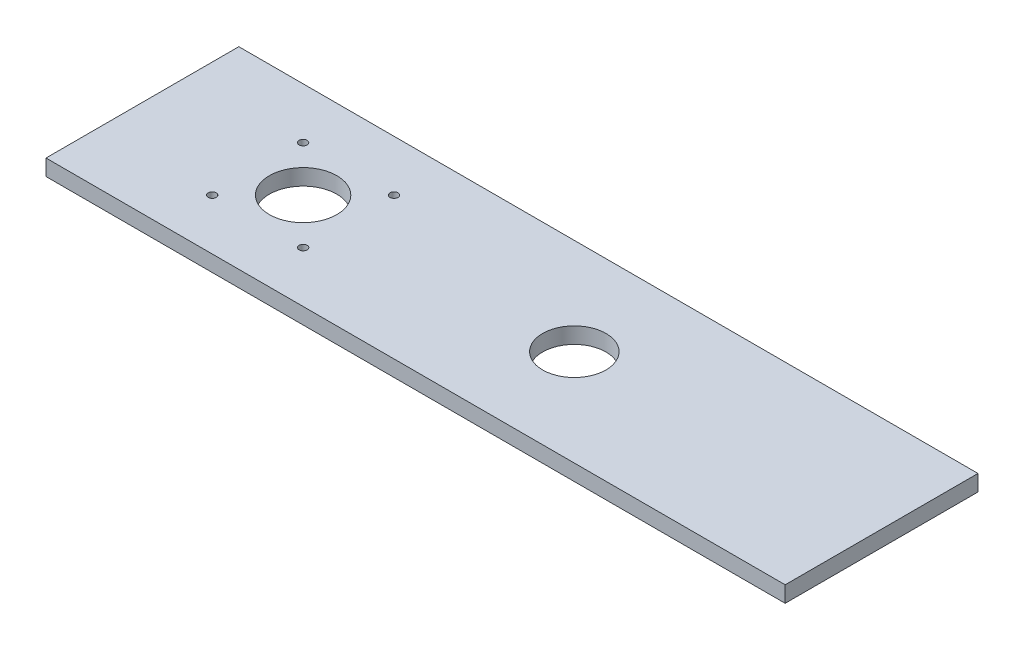
SolidWorks part; units mm, degrees
ref_plane "Front Plane" through (0, 0, 0) normal (0, 0, 1) x (1, 0, 0)
ref_plane "Top Plane" through (0, 0, 0) normal (0, 1, 0) x (1, 0, 0)
ref_plane "Right Plane" through (0, 0, 0) normal (1, 0, 0) x (0, 0, -1)
sketch "Sketch1" plane through (0, 0, 0) normal (0, 1, 0) x (1, 0, 0)
  line L0 (-50, 30) -> (180, 30)
  line L2 (-50, 30) -> (-50, -30)
  line L4 (180, 30) -> (180, -30)
  line L5 (180, -30) -> (-50, -30)
  circle A0 centre (0, 0) radius 10.5
  circle A3 centre (84.3856, 0) radius 9.8483
  point P0 (0, 0)
  dimension "D1" = 21
  dimension "D2" = 230
  dimension "D3" = 60
  dimension "D4" = 50
extrude "Boss-Extrude1" add sketch "Sketch1" along normal blind 5
hole_wizard "M3x0.5 Tapped Hole1" positions "Sketch3" profile "Sketch4" tap size "M3x0.5" standard "ANSI Metric" end condition through all
sketch "Sketch3" plane through (0, 5, 0) normal (0, 1, 0) x (1, 0, 0)
  line L4 (-14.1421, 14.1421) -> (0, 0) construction
  line L5 (0, 0) -> (0, 30) construction
  line L6 (180, 30) -> (-50, 30) construction
  point P0 (-14.1421, 14.1421)
  point P36 (14.1421, 14.1421)
  point P37 (14.1421, -14.1421)
  point P38 (-14.1421, -14.1421)
  point P39 (0, 0)
  dimension "D1" = 4
  dimension "D2" = 45
  dimension "D3" = 20
sketch "Sketch4" plane through (-14.1421, 5, -14.1421) normal (1, 0, 0) x (0, 0, 1)
  line L0 (0, 0) -> (0, 5)
  line L1 (0, 5) -> (1.25, 5)
  line L2 (1.25, 5) -> (1.25, 0)
  line L5 (1.25, 0) -> (0, 0)
  line L11 (0, -6.35) -> (0, 107.95) construction
  dimension "Thru Tap Drill Dia." = 2.5
  dimension "Thru Tap Drill Depth" = 5
cosmetic thread "Hole Thread1" parameters "D2"=3
cosmetic thread "Hole Thread2" parameters "D2"=3
cosmetic thread "Hole Thread3" parameters "D2"=3
cosmetic thread "Hole Thread4" parameters "D2"=3
